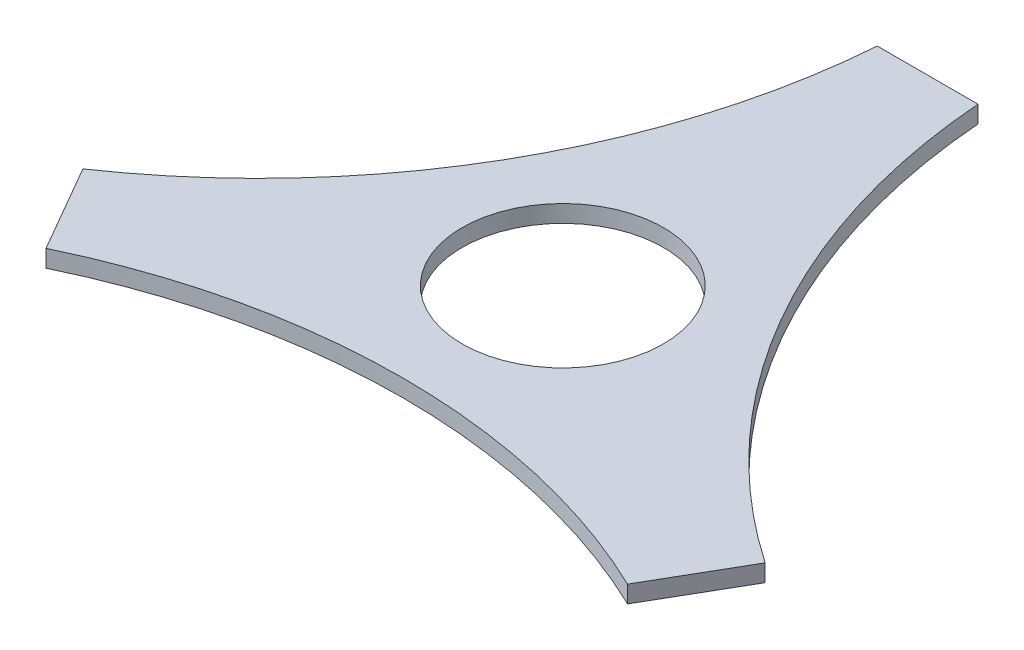
SolidWorks part; units mm, degrees
material "AISI 4340 Steel, normalized"
ref_plane "Front Plane" through (0, 0, 0) normal (0, 0, 1) x (1, 0, 0)
ref_plane "Top Plane" through (0, 0, 0) normal (0, 1, 0) x (1, 0, 0)
ref_plane "Right Plane" through (0, 0, 0) normal (1, 0, 0) x (0, 0, -1)
sketch "Sketch1" plane through (0, 0, 0) normal (0, 1, 0) x (1, 0, 0)
  line L0 (0, 0) -> (0, 68.9993) construction
  line L2 (9.525, 5.4993) -> (64.5176, -26.2507)
  line L3 (64.5176, -26.2507) -> (54.9926, -42.7485)
  line L5 (-9.525, 5.4993) -> (-9.525, 68.9993)
  line L6 (-9.525, 68.9993) -> (9.525, 68.9993)
  line L7 (9.525, 5.4993) -> (9.525, 68.9993)
  line L8 (0, -10.9985) -> (54.9926, -42.7485)
  line L9 (0, 0) -> (59.7551, -34.4996) construction
  line L11 (0, -10.9985) -> (-54.9926, -42.7485)
  line L12 (-54.9926, -42.7485) -> (-64.5176, -26.2507)
  line L13 (-9.525, 5.4993) -> (-64.5176, -26.2507)
  line L14 (0, 0) -> (-59.7551, -34.4996) construction
  arc A0 (9.525, 68.9993) -> (64.5176, -26.2507) centre (136.1606, 78.6124) ccw
  arc A1 (54.9926, -42.7485) -> (-54.9926, -42.7485) centre (0, -157.2248) ccw
  arc A2 (-64.5176, -26.2507) -> (-9.525, 68.9993) centre (-136.1606, 78.6124) ccw
  circle A3 centre (0, 0) radius 19.05 construction
  point P11 (0, 68.9993)
  point P20 (0, 0)
  dimension "D4" = 127
  dimension "D5" = 38.1
  dimension "D1" = 3
  dimension "D2" = 63.5
  dimension "D3" = 19.05
extrude "Boss-Extrude1" add sketch "Sketch1" along normal mid plane 3.2512 contours A2 L13 L5 | L5 L13 L12 L11 L8 L3 L2 L7 L6 | A1 L8 L11 | A0 L7 L2
sketch "Sketch3" plane through (0, 1.6256, 0) normal (0, 1, 0) x (1, 0, 0)
  circle A0 centre (0, 0) radius 19.05 construction
  circle A1 centre (0, 0) radius 19.05
extrude "Cut-Extrude2" cut sketch "Sketch3" against normal through all
